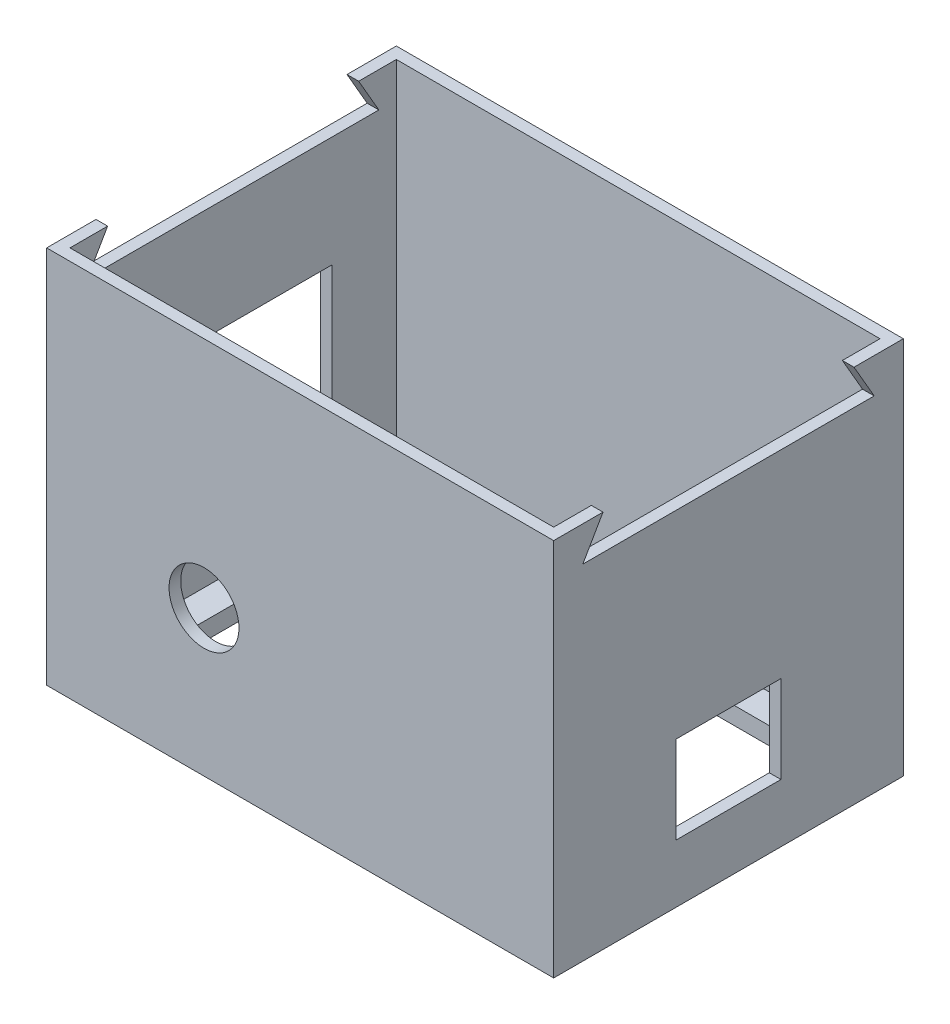
SolidWorks part; units mm, degrees
ref_plane "Front Plane" through (0, 0, 0) normal (0, 0, 1) x (1, 0, 0)
ref_plane "Top Plane" through (0, 0, 0) normal (0, 1, 0) x (1, 0, 0)
ref_plane "Right Plane" through (0, 0, 0) normal (1, 0, 0) x (0, 0, -1)
sketch "Sketch1" plane through (0, 0, 0) normal (0, 1, 0) x (1, 0, 0)
  line L1 (0, 0) -> (-87, 0)
  line L2 (0, 0) -> (0, 60)
  line L3 (0, 60) -> (-87, 60)
  line L4 (-87, 0) -> (-87, 60)
  dimension "D1" = 60
  dimension "D2" = 87
extrude "Boss-Extrude1" add sketch "Sketch1" along normal blind 65
sketch "Sketch2" plane through (0, 65, 0) normal (0, 1, 0) x (1, 0, 0)
  line L0 (0, 0) -> (0, 60) construction
  line L1 (-2, 2) -> (-85, 2)
  line L2 (-2, 2) -> (-2, 58)
  line L3 (-2, 58) -> (-85, 58)
  line L4 (-85, 2) -> (-85, 58)
  line L5 (-87, 0) -> (0, 0) construction
  line L6 (-87, 60) -> (-87, 0) construction
  line L7 (0, 60) -> (-87, 60) construction
  dimension "D1" = 2
  dimension "D2" = 2
  dimension "D3" = 2
  dimension "D4" = 2
extrude "Cut-Extrude1" cut sketch "Sketch2" against normal blind 62
sketch "Sketch3" plane through (0, 0, 0) normal (1, 0, 0) x (0, 0, -1)
  line L0 (0, 0) -> (60, 0) construction
  line L1 (39, 10) -> (21, 10)
  line L2 (39, 10) -> (39, 25)
  line L3 (39, 25) -> (21, 25)
  line L4 (21, 10) -> (21, 25)
  line L5 (30, 25) -> (30, 34.0106) construction
  line L6 (0, 65) -> (0, 0) construction
  dimension "D1" = 10
  dimension "D2" = 25
  dimension "D3" = 18
  dimension "D4" = 30
extrude "Cut-Extrude2" cut sketch "Sketch3" against normal blind 57
sketch "Sketch4" plane through (0, 0, 0) normal (0, 0, 1) x (1, 0, 0)
  line L0 (0, 65) -> (0, 0) construction
  line L1 (-87, 0) -> (0, 0) construction
  circle A0 centre (-60, 25) radius 6
  dimension "D1" = 12
  dimension "D2" = 60
  dimension "D3" = 25
extrude "Cut-Extrude3" cut sketch "Sketch4" against normal blind 24
sketch "Sketch5" plane through (-87, 0, 0) normal (-1, 0, 0) x (0, 0, 1)
  line L0 (-60, 0) -> (0, 0) construction
  line L1 (-13, 40) -> (-47, 40)
  line L2 (-13, 40) -> (-13, 10)
  line L3 (-13, 10) -> (-47, 10)
  line L4 (-47, 40) -> (-47, 10)
  line L5 (0, 65) -> (0, 0) construction
  line L6 (-60, 65) -> (-60, 0) construction
  dimension "D1" = 40
  dimension "D2" = 10
  dimension "D3" = 13
  dimension "D4" = 13
extrude "Cut-Extrude4" cut sketch "Sketch5" against normal blind 24
sketch "Sketch6" plane through (0, 0, 0) normal (1, 0, 0) x (0, 0, -1)
  line L0 (8.4641, 65) -> (5, 59)
  line L1 (0, 65) -> (60, 65) construction
  line L2 (5, 59) -> (55, 59)
  line L3 (55, 59) -> (51.5359, 65)
  line L4 (51.5359, 65) -> (8.4641, 65)
  line L5 (60, 65) -> (60, 0) construction
  line L6 (0, 65) -> (0, 0) construction
  dimension "D1" = 60
  dimension "D2" = 60
  dimension "D3" = 5
  dimension "D4" = 5
  dimension "D5" = 6
extrude "Cut-Extrude5" cut sketch "Sketch6" against normal blind 117
sketch "Sketch7" plane through (0, 3, 0) normal (0, 1, 0) x (1, 0, 0)
  line L0 (-2, 5) -> (-2, 55) construction
  line L1 (-7, 7) -> (-80, 7)
  line L2 (-7, 7) -> (-7, 53)
  line L3 (-7, 53) -> (-80, 53)
  line L4 (-80, 7) -> (-80, 53)
  line L5 (-85, 55) -> (-85, 5) construction
  line L6 (-2, 58) -> (-85, 58) construction
  line L7 (-85, 2) -> (-2, 2) construction
  dimension "D1" = 5
  dimension "D2" = 5
  dimension "D3" = 5
  dimension "D4" = 5
extrude "Cut-Extrude6" cut sketch "Sketch7" against normal blind 10
